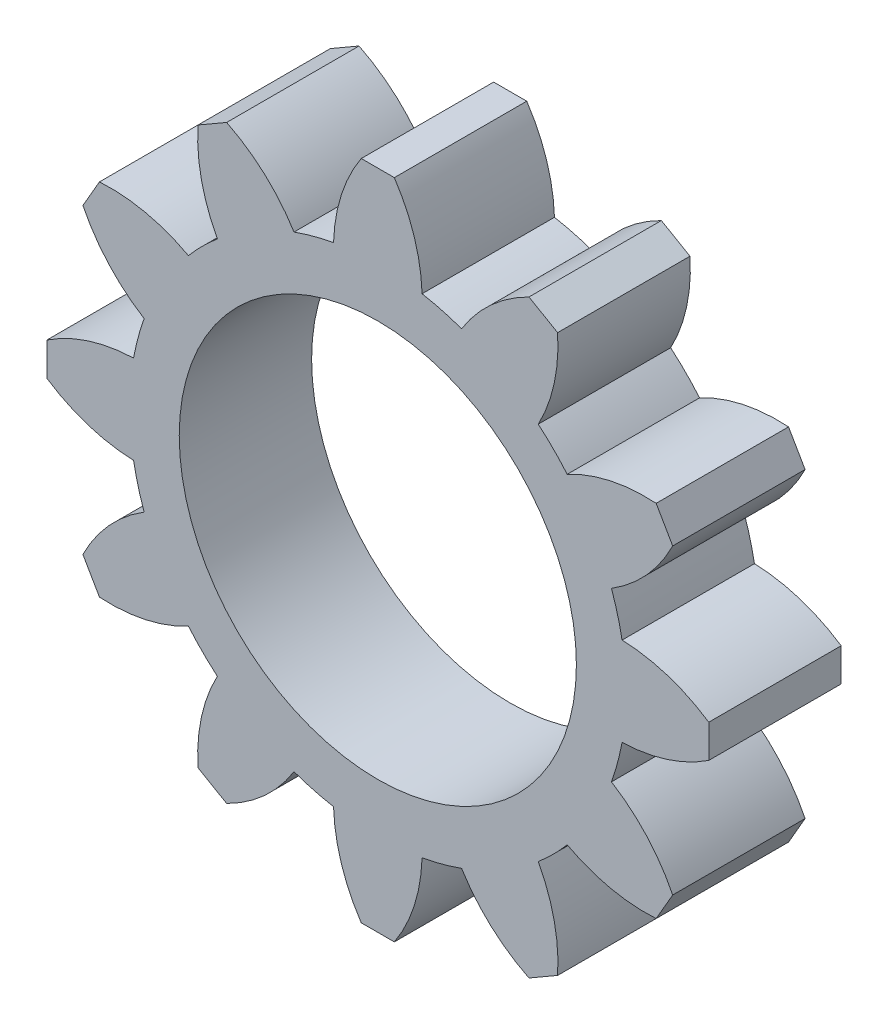
SolidWorks part; units mm, degrees
material "Brass"
ref_plane "Front Plane" through (0, 0, 0) normal (0, 0, 1) x (1, 0, 0)
ref_plane "Top Plane" through (0, 0, 0) normal (0, 1, 0) x (1, 0, 0)
ref_plane "Right Plane" through (0, 0, 0) normal (1, 0, 0) x (0, 0, -1)
sketch "Sketch1" plane through (0, 0, 0) normal (0, 0, 1) x (1, 0, 0)
  line L0 (-1, 20) -> (1, 20)
  line L1 (-2.675, 14.7596) -> (2.675, 14.7596) construction
  line L2 (9.134, 17.8205) -> (10.866, 16.8205)
  line L3 (16.8205, 10.866) -> (17.8205, 9.134)
  line L4 (20, 1) -> (20, -1)
  line L5 (17.8205, -9.134) -> (16.8205, -10.866)
  line L6 (10.866, -16.8205) -> (9.134, -17.8205)
  line L7 (1, -20) -> (-1, -20)
  line L8 (-9.134, -17.8205) -> (-10.866, -16.8205)
  line L9 (-16.8205, -10.866) -> (-17.8205, -9.134)
  line L10 (-20, -1) -> (-20, 1)
  line L11 (-17.8205, 9.134) -> (-16.8205, 10.866)
  line L12 (-10.866, 16.8205) -> (-9.134, 17.8205)
  circle A0 centre (0, 0) radius 12
  arc A1 (-9.6964, 11.4446) -> (-11.4446, 9.6964) centre (0, 0) ccw
  arc A2 (-1, 20) -> (-2.675, 14.7596) centre (7.3203, 14.4527) ccw
  arc A3 (1, 20) -> (2.675, 14.7596) centre (-7.3203, 14.4527) cw
  arc A4 (10.866, 16.8205) -> (9.6964, 11.4446) centre (0.8868, 16.1765) cw
  arc A5 (9.134, 17.8205) -> (5.0632, 14.1196) centre (13.5659, 8.8562) ccw
  arc A6 (17.8205, 9.134) -> (14.1196, 5.0632) centre (8.8562, 13.5659) cw
  arc A7 (16.8205, 10.866) -> (11.4446, 9.6964) centre (16.1765, 0.8868) ccw
  arc A8 (20, -1) -> (14.7596, -2.675) centre (14.4527, 7.3203) cw
  arc A9 (20, 1) -> (14.7596, 2.675) centre (14.4527, -7.3203) ccw
  arc A10 (16.8205, -10.866) -> (11.4446, -9.6964) centre (16.1765, -0.8868) cw
  arc A11 (17.8205, -9.134) -> (14.1196, -5.0632) centre (8.8562, -13.5659) ccw
  arc A12 (9.134, -17.8205) -> (5.0632, -14.1196) centre (13.5659, -8.8562) cw
  arc A13 (10.866, -16.8205) -> (9.6964, -11.4446) centre (0.8868, -16.1765) ccw
  arc A14 (-1, -20) -> (-2.675, -14.7596) centre (7.3203, -14.4527) cw
  arc A15 (1, -20) -> (2.675, -14.7596) centre (-7.3203, -14.4527) ccw
  arc A16 (-10.866, -16.8205) -> (-9.6964, -11.4446) centre (-0.8868, -16.1765) cw
  arc A17 (-9.134, -17.8205) -> (-5.0632, -14.1196) centre (-13.5659, -8.8562) ccw
  arc A18 (-17.8205, -9.134) -> (-14.1196, -5.0632) centre (-8.8562, -13.5659) cw
  arc A19 (-16.8205, -10.866) -> (-11.4446, -9.6964) centre (-16.1765, -0.8868) ccw
  arc A20 (-20, 1) -> (-14.7596, 2.675) centre (-14.4527, -7.3203) cw
  arc A21 (-20, -1) -> (-14.7596, -2.675) centre (-14.4527, 7.3203) ccw
  arc A22 (-16.8205, 10.866) -> (-11.4446, 9.6964) centre (-16.1765, 0.8868) cw
  arc A23 (-17.8205, 9.134) -> (-14.1196, 5.0632) centre (-8.8562, 13.5659) ccw
  arc A24 (-9.134, 17.8205) -> (-5.0632, 14.1196) centre (-13.5659, 8.8562) cw
  arc A25 (-10.866, 16.8205) -> (-9.6964, 11.4446) centre (-0.8868, 16.1765) ccw
  arc A26 (-2.675, 14.7596) -> (-5.0632, 14.1196) centre (0, 0) ccw
  arc A27 (5.0632, 14.1196) -> (2.675, 14.7596) centre (0, 0) ccw
  arc A28 (11.4446, 9.6964) -> (9.6964, 11.4446) centre (0, 0) ccw
  arc A29 (14.7596, 2.675) -> (14.1196, 5.0632) centre (0, 0) ccw
  arc A30 (14.1196, -5.0632) -> (14.7596, -2.675) centre (0, 0) ccw
  arc A31 (9.6964, -11.4446) -> (11.4446, -9.6964) centre (0, 0) ccw
  arc A32 (2.675, -14.7596) -> (5.0632, -14.1196) centre (0, 0) ccw
  arc A33 (-5.0632, -14.1196) -> (-2.675, -14.7596) centre (0, 0) ccw
  arc A34 (-11.4446, -9.6964) -> (-9.6964, -11.4446) centre (0, 0) ccw
  arc A35 (-14.7596, -2.675) -> (-14.1196, -5.0632) centre (0, 0) ccw
  arc A36 (-14.1196, 5.0632) -> (-14.7596, 2.675) centre (0, 0) ccw
  point P6 (0, 20)
  point P11 (0, 14.7596)
  point P80 (0, 0)
  dimension "D1" = 24
  dimension "D2" = 30
  dimension "D4" = 10
  dimension "D3" = 2
  dimension "D5" = 5.35
  dimension "D6" = 20
  dimension "D7" = 12
extrude "Boss-Extrude1" add sketch "Sketch1" along normal blind 8
